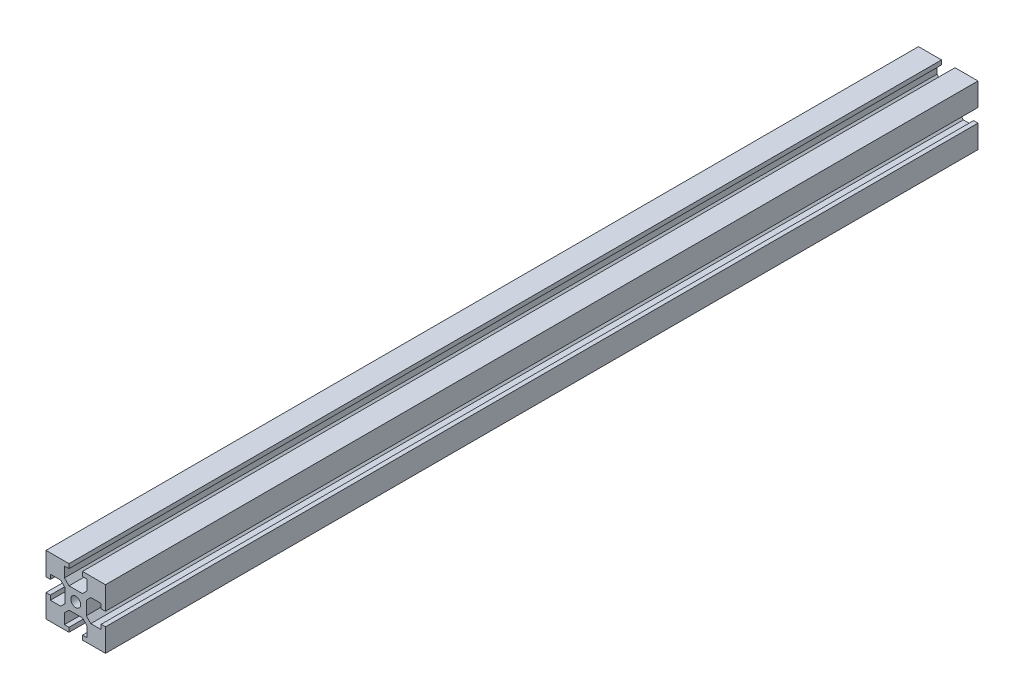
SolidWorks part; units mm, degrees
ref_plane "正面" through (0, 0, 0) normal (0, 0, 1) x (1, 0, 0)
ref_plane "平面" through (0, 0, 0) normal (0, 1, 0) x (1, 0, 0)
ref_plane "右側面" through (0, 0, 0) normal (1, 0, 0) x (0, 0, -1)
sketch "ｽｹｯﾁ2" plane through (0, 0, 0) normal (0, 0, 1) x (1, 0, 0)
  line L0 (0, 0) -> (0, 7.5) construction
  line L1 (-7.5, -7.5) -> (7.5, -7.5) construction
  line L2 (-7.5, -7.5) -> (-7.5, 7.5) construction
  line L3 (-7.5, 7.5) -> (7.5, 7.5) construction
  line L4 (7.5, -7.5) -> (7.5, 7.5) construction
  line L5 (-7.5, -7.5) -> (7.5, 7.5) construction
  line L6 (-7.5, 7.5) -> (7.5, -7.5) construction
  line L8 (1.7, 2.65) -> (-1.7, 2.65)
  line L9 (-2.85, 3.8) -> (2.85, 3.8) construction
  line L10 (-2.85, 6.4) -> (-2.85, 3.8)
  line L11 (2.85, 6.4) -> (2.85, 3.8)
  line L12 (-2.85, 3.8) -> (-1.7, 2.65)
  line L13 (1.7, 2.65) -> (2.85, 3.8)
  line L14 (-2.85, 6.4) -> (-1.7, 6.4)
  line L15 (-1.7, 6.4) -> (-1.7, 7.5)
  line L16 (-1.7, 7.5) -> (-7.5, 7.5)
  line L17 (2.85, 6.4) -> (1.7, 6.4)
  line L18 (1.7, 6.4) -> (1.7, 7.5)
  line L19 (1.7, 7.5) -> (7.5, 7.5)
  line L20 (3.8, 2.85) -> (2.65, 1.7)
  line L21 (2.65, -1.7) -> (2.65, 1.7)
  line L22 (2.65, -1.7) -> (3.8, -2.85)
  line L23 (6.4, -2.85) -> (6.4, -1.7)
  line L24 (6.4, -2.85) -> (3.8, -2.85)
  line L25 (6.4, -1.7) -> (7.5, -1.7)
  line L26 (7.5, -1.7) -> (7.5, -7.5)
  line L27 (6.4, 1.7) -> (7.5, 1.7)
  line L28 (7.5, 1.7) -> (7.5, 7.5)
  line L29 (6.4, 2.85) -> (6.4, 1.7)
  line L30 (6.4, 2.85) -> (3.8, 2.85)
  line L31 (2.85, -3.8) -> (1.7, -2.65)
  line L32 (-1.7, -2.65) -> (1.7, -2.65)
  line L33 (-1.7, -2.65) -> (-2.85, -3.8)
  line L34 (-2.85, -6.4) -> (-1.7, -6.4)
  line L35 (-2.85, -6.4) -> (-2.85, -3.8)
  line L36 (-1.7, -6.4) -> (-1.7, -7.5)
  line L37 (-1.7, -7.5) -> (-7.5, -7.5)
  line L38 (1.7, -6.4) -> (1.7, -7.5)
  line L39 (1.7, -7.5) -> (7.5, -7.5)
  line L40 (2.85, -6.4) -> (1.7, -6.4)
  line L41 (2.85, -6.4) -> (2.85, -3.8)
  line L42 (-3.8, -2.85) -> (-2.65, -1.7)
  line L43 (-2.65, 1.7) -> (-2.65, -1.7)
  line L44 (-2.65, 1.7) -> (-3.8, 2.85)
  line L45 (-6.4, 2.85) -> (-6.4, 1.7)
  line L46 (-6.4, 2.85) -> (-3.8, 2.85)
  line L47 (-6.4, 1.7) -> (-7.5, 1.7)
  line L48 (-7.5, 1.7) -> (-7.5, 7.5)
  line L49 (-6.4, -1.7) -> (-7.5, -1.7)
  line L50 (-7.5, -1.7) -> (-7.5, -7.5)
  line L51 (-6.4, -2.85) -> (-6.4, -1.7)
  line L52 (-6.4, -2.85) -> (-3.8, -2.85)
  circle A0 centre (0, 0) radius 1.25
  point P0 (0, 0)
  point P11 (0, 7.5)
  point P14 (0, 2.65)
  point P17 (0, 3.8)
  dimension "D8" = 2.5
  dimension "D1" = 15
  dimension "D2" = 3.4
  dimension "D3" = 1.1
  dimension "D4" = 2.6
  dimension "D5" = 5.7
  dimension "D6" = 3.4
  dimension "D7" = 4
extrude "ﾎﾞｽ - 押し出し1" add sketch "ｽｹｯﾁ2" along normal blind 220
